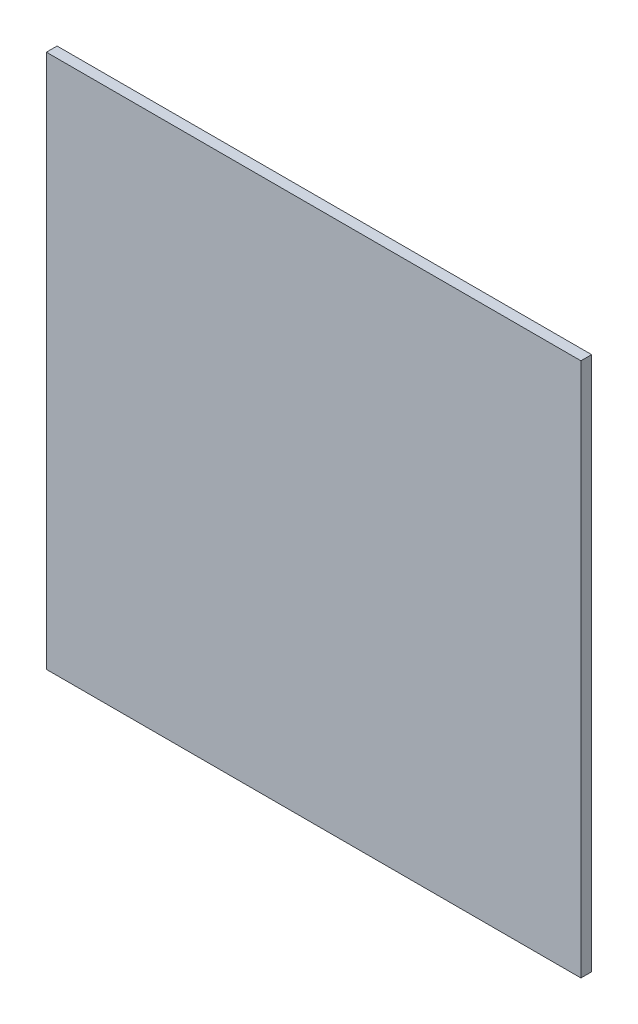
SolidWorks part; units mm, degrees
ref_plane "Front Plane" through (0, 0, 0) normal (0, 0, 1) x (1, 0, 0)
ref_plane "Top Plane" through (0, 0, 0) normal (0, 1, 0) x (1, 0, 0)
ref_plane "Right Plane" through (0, 0, 0) normal (1, 0, 0) x (0, 0, -1)
sketch "Sketch1" plane through (0, 0, 0) normal (0, 0, 1) x (1, 0, 0)
  line L1 (-250, 250) -> (250, 250)
  line L2 (-250, 250) -> (-250, -250)
  line L3 (-250, -250) -> (250, -250)
  line L4 (250, 250) -> (250, -250)
  line L5 (-250, 250) -> (250, -250) construction
  line L6 (-250, -250) -> (250, 250) construction
  point P0 (0, 0)
  dimension "D1" = 500
  dimension "D2" = 500
extrude "Boss-Extrude1" add sketch "Sketch1" along normal blind 10 contours L1 L4 L3 L2
sketch "Sketch2" plane through (0, 0, 10) normal (0, 0, 1) x (1, 0, 0)
  line L0 (-164.4838, 13.2295) -> (24.8994, 165.8379)
